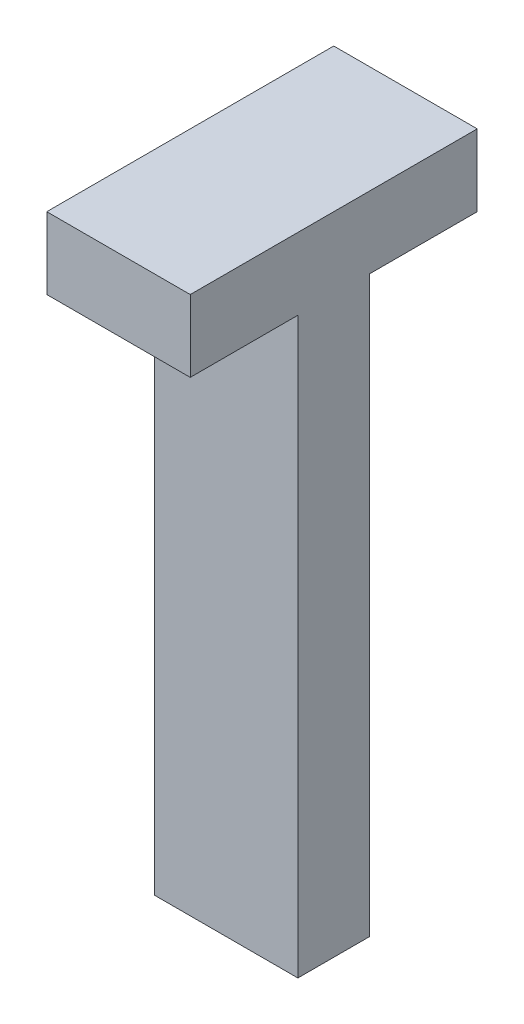
SolidWorks part; units mm, degrees
ref_plane "Front Plane" through (0, 0, 0) normal (1, 0, 0) x (0, 1, 0)
ref_plane "Top Plane" through (0, 0, 0) normal (0, 0, 1) x (0, 1, 0)
ref_plane "Right Plane" through (0, 0, 0) normal (0, 1, 0) x (-1, 0, 0)
sketch "Sketch2" plane through (0, 0, 0) normal (1, 0, 0) x (0, 1, 0)
  line L0 (0, 0) -> (0, 40)
  line L1 (0, 40) -> (-10, 40)
  line L2 (-10, 40) -> (-10, 25)
  line L3 (-10, 25) -> (-90, 25)
  line L4 (-90, 25) -> (-90, 15)
  line L5 (-90, 15) -> (-10, 15)
  line L6 (-10, 15) -> (-10, 0)
  line L7 (-10, 0) -> (0, 0)
  dimension "D1" = 40
  dimension "D2" = 80
  dimension "D3" = 10
  dimension "D4" = 15
  dimension "D5" = 10
extrude "Boss-Extrude1" add sketch "Sketch2" along normal blind 20
